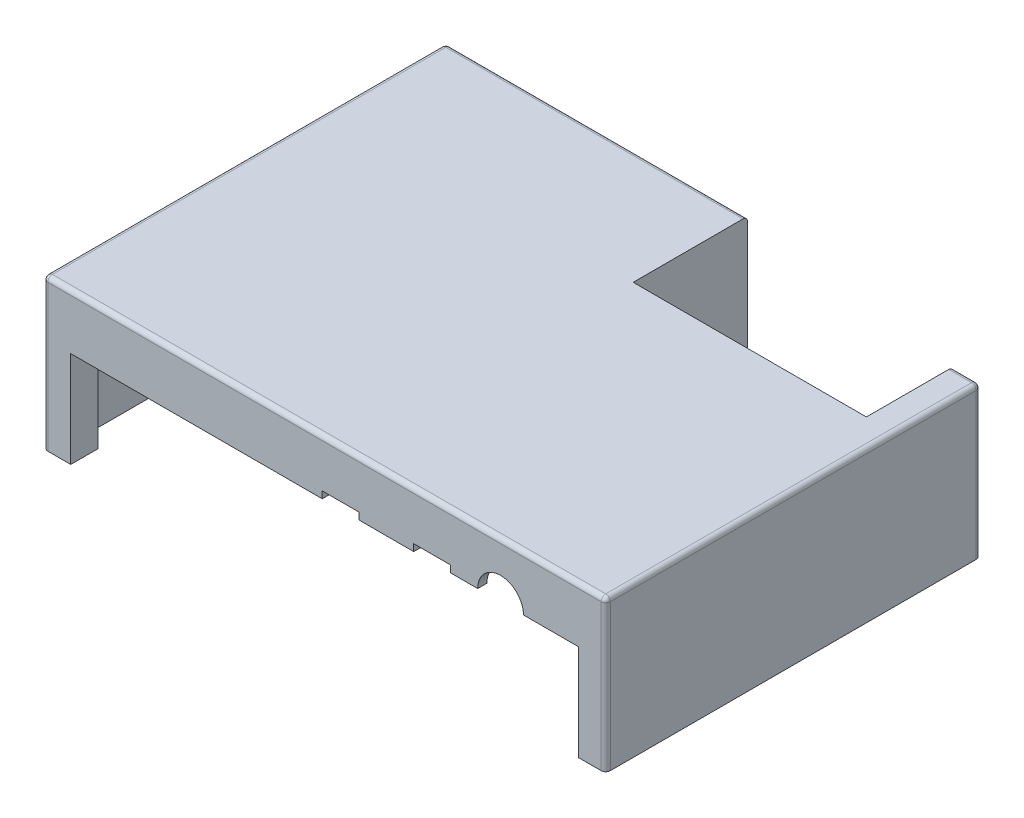
SolidWorks part; units mm, degrees
ref_plane "Front Plane" through (0, 0, 0) normal (0, 0, 1) x (1, 0, 0)
ref_plane "Top Plane" through (0, 0, 0) normal (0, 1, 0) x (1, 0, 0)
ref_plane "Right Plane" through (0, 0, 0) normal (1, 0, 0) x (0, 0, -1)
sketch "Sketch2" plane through (0, 0, 0) normal (0, 1, 0) x (1, 0, 0)
  line L5 (-61.5, 44) -> (61.5, 44)
  line L6 (-61.5, 44) -> (-61.5, -44)
  line L7 (-61.5, -44) -> (61.5, -44)
  line L8 (61.5, 44) -> (61.5, -44)
  line L9 (-61.5, 44) -> (61.5, -44) construction
  line L10 (-61.5, -44) -> (61.5, 44) construction
  point P0 (0, 0)
  dimension "D1" = 123
  dimension "D2" = 88
extrude "Boss-Extrude1" add sketch "Sketch2" against normal blind 2
sketch "Sketch3" plane through (0, 0, 0) normal (0, 1, 0) x (1, 0, 0)
  line L1 (55.5, 44) -> (61.5, 44)
  line L2 (55.5, 44) -> (55.5, 38)
  line L3 (55.5, 38) -> (61.5, 38)
  line L4 (61.5, 44) -> (61.5, 38)
  line L5 (55.5, 44) -> (61.5, 38) construction
  line L6 (55.5, 38) -> (61.5, 44) construction
  line L7 (4.5, 44) -> (55.5, 44)
  line L8 (4.5, 44) -> (4.5, 19)
  line L9 (4.5, 19) -> (55.5, 19)
  line L10 (55.5, 44) -> (55.5, 19)
  line L11 (4.5, 44) -> (55.5, 19) construction
  line L12 (4.5, 19) -> (55.5, 44) construction
  point P0 (58.5, 41)
  point P7 (30, 31.5)
  line M7 (61.5, -44) -> (61.5, 44)
  line M8 (61.5, 44) -> (-61.5, 44)
  dimension "D1" = 6
  dimension "D2" = 6
  dimension "D3" = 51
  dimension "D4" = 25
extrude "Cut-Extrude1" cut sketch "Sketch3" against normal blind 2 contours L10 L2 L8 L9 M8 | L2 L3 M7 M8
sketch "Sketch4" plane through (0, 0, 0) normal (0, 1, 0) x (1, 0, 0)
  line L0 (55.5, -38) -> (61.5, -38)
  line L1 (55.5, 38) -> (61.5, 38)
  line L2 (55.5, 38) -> (55.5, 32)
  line L3 (55.5, 32) -> (61.5, 32)
  line L4 (61.5, 38) -> (61.5, 32)
  line L5 (55.5, 38) -> (61.5, 32) construction
  line L6 (55.5, 32) -> (61.5, 38) construction
  line L7 (61.5, 32) -> (59.5, 32)
  line L8 (61.5, 32) -> (61.5, -38)
  line L9 (61.5, -38) -> (59.5, -38)
  line L10 (59.5, 32) -> (59.5, -38)
  line L11 (61.5, 32) -> (59.5, -38) construction
  line L12 (61.5, -38) -> (59.5, 32) construction
  line L13 (55.5, -38) -> (55.5, -44)
  line L14 (55.5, -44) -> (61.5, -44)
  line L15 (61.5, -38) -> (61.5, -44)
  line L16 (55.5, -38) -> (61.5, -44) construction
  line L17 (55.5, -44) -> (61.5, -38) construction
  line L18 (61.5, -44) -> (59.5, -44)
  line L24 (-55.5, -42) -> (55.5, -42)
  line L25 (-55.5, -42) -> (-55.5, -44)
  line L26 (-61.5, -38) -> (-55.5, -38)
  line L27 (-61.5, -38) -> (-61.5, -44)
  line L28 (-61.5, -44) -> (-55.5, -44)
  line L29 (-55.5, -38) -> (-55.5, -44)
  line L30 (-61.5, -38) -> (-55.5, -44) construction
  line L31 (-61.5, -44) -> (-55.5, -38) construction
  line L32 (-55.5, -44) -> (-57.5, -44)
  line L37 (-55.5, -44) -> (55.5, -44)
  line L38 (55.5, -42) -> (55.5, -44)
  line L39 (-55.5, -42) -> (55.5, -44) construction
  line L44 (-61.5, 44) -> (-61.5, 38)
  line L45 (-55.5, -44) -> (55.5, -42) construction
  line L46 (-61.5, 38) -> (-59.5, 38)
  line L47 (-61.5, 44) -> (-55.5, 44)
  line L49 (-61.5, 38) -> (-55.5, 38)
  line L50 (-55.5, 44) -> (-55.5, 38)
  line L51 (-61.5, 44) -> (-55.5, 38) construction
  line L52 (-61.5, 38) -> (-55.5, 44) construction
  line L53 (-55.5, 38) -> (-57.5, 38)
  line L54 (-61.5, 38) -> (-61.5, -38)
  line L55 (-61.5, -38) -> (-59.5, -38)
  line L56 (-59.5, 38) -> (-59.5, -38)
  line L57 (-55.5, 44) -> (4.5, 44)
  line L58 (-55.5, 44) -> (-55.5, 42)
  line L59 (-55.5, 42) -> (4.5, 42)
  line L60 (4.5, 44) -> (4.5, 42)
  line L61 (2.5, 42) -> (4.5, 42)
  line L62 (2.5, 42) -> (2.5, 17)
  line L63 (2.5, 17) -> (4.5, 17)
  line L64 (4.5, 42) -> (4.5, 17)
  line L65 (4.5, 19) -> (55.5, 19)
  line L66 (4.5, 19) -> (4.5, 17)
  line L67 (4.5, 17) -> (55.5, 17)
  line L68 (55.5, 19) -> (55.5, 17)
  point P0 (55.5, 38)
  point P8 (54.7765, -38.1599)
  point P14 (60.5, -3)
  point P22 (0, -43)
  point P24 (58.5, -41)
  point P31 (-63.8243, -36.7219)
  point P56 (-56.1941, 43.3453)
  line M43 (4.5, 19) -> (4.5, 44)
  line M44 (4.5, 44) -> (-61.5, 44)
  line M45 (-61.5, 44) -> (-61.5, -44)
  line M46 (-61.5, -44) -> (61.5, -44)
  line M47 (61.5, -44) -> (61.5, 38)
  line M48 (61.5, 38) -> (55.5, 38)
  line M49 (55.5, 38) -> (55.5, 19)
  line M50 (55.5, 19) -> (4.5, 19)
  dimension "D1" = 6
  dimension "D2" = 6
  dimension "D4" = 2
  dimension "D5" = 2
  dimension "D7" = 2
  dimension "D10" = 2
  dimension "D3" = 6
  dimension "D6" = 6
  dimension "D8" = 6
  dimension "D9" = 6
  dimension "D11" = 6
  dimension "D12" = 6
  dimension "D13" = 2
  dimension "D14" = 111
  dimension "D15" = 2
  dimension "D16" = 76
  dimension "D17" = 60
  dimension "D18" = 2
  dimension "D19" = 25
  dimension "D20" = 2
  dimension "D21" = 2
  dimension "D22" = 51
extrude "Boss-Extrude2" add sketch "Sketch4" against normal blind 33 contours L50 L59 M43 M44 | L50 L46 L49 M44 M45 | L56 L46 L26 M45 | L68 L64 L67 M50 | L3 M49 M47 M48 | L29 L26 L28 L25 M45 M46 | L24 L25 L13 M46 | L0 L13 L14 M46 M47 | L3 L10 L0 M47
sketch "Sketch5" plane through (0, 0, -44) normal (0, 0, -1) x (-1, 0, 0)
  line L0 (-4.5, -33) -> (61.5, -33) construction
  line L1 (61.5, -33) -> (61.5, 0) construction
  line L3 (10.5, -9) -> (23.5, -9)
  line L4 (10.5, -9) -> (10.5, -17)
  line L5 (10.5, -17) -> (23.5, -17)
  line L6 (23.5, -9) -> (23.5, -17)
  circle A0 centre (35.5, -12) radius 3
  point P10 (23.5, -13)
  dimension "D1" = 6
  dimension "D2" = 21
  dimension "D3" = 26
  dimension "D4" = 13
  dimension "D5" = 8
  dimension "D6" = 38
  dimension "D7" = 20
extrude "Cut-Extrude2" cut sketch "Sketch5" against normal up to surface (2 mm away) and the other way through all contours L6 L3 L4 L5 | A0 up to face at (-26.5, -17.5, -42)
sketch "Sketch6" plane through (0, 0, 44) normal (0, 0, 1) x (1, 0, 0)
  line L0 (-61.5, -33) -> (61.5, -33) construction
  line L1 (-55.5, -12) -> (55.5, -12)
  line L2 (-55.5, -12) -> (-55.5, -33)
  line L3 (-55.5, -33) -> (55.5, -33)
  line L4 (55.5, -12) -> (55.5, -33)
  line L5 (-61.5, -33) -> (-61.5, 0) construction
  dimension "D3" = 6
  dimension "D1" = 111
  dimension "D2" = 21
extrude "Cut-Extrude3" cut sketch "Sketch6" against normal up to surface (2 mm away) up to face at (0, -17.5, 42)
sketch "Sketch7" plane through (0, 0, 44) normal (0, 0, 1) x (1, 0, 0)
  line L0 (33.5, -12) -> (43.5, -12)
  line L1 (-0.5, -10.5) -> (7.5, -10.5)
  line L2 (61.5, -33) -> (61.5, 0) construction
  line L3 (55.5, -12) -> (-55.5, -12) construction
  line L4 (19.5, -10.5) -> (27.5, -10.5)
  line L5 (19.5, -10.5) -> (19.5, -12)
  line L6 (19.5, -12) -> (27.5, -12)
  line L7 (27.5, -10.5) -> (27.5, -12)
  line L8 (-0.5, -10.5) -> (-0.5, -12)
  line L9 (-0.5, -12) -> (7.5, -12)
  line L10 (7.5, -10.5) -> (7.5, -12)
  arc A0 (43.5, -12) -> (33.5, -12) centre (38.5, -12) ccw
  dimension "D1" = 10
  dimension "D2" = 23
  dimension "D3" = 8
  dimension "D4" = 1.5
  dimension "D5" = 34
  dimension "D7" = 20
  dimension "D6" = 2
extrude "Cut-Extrude4" cut sketch "Sketch7" against normal up to surface (2 mm away) up to face at (0, -7, 42)
sketch "Sketch10" plane through (0, -33, 0) normal (0, -1, 0) x (1, 0, 0)
  line L0 (-61.5, 44) -> (-55.5, 38) construction
  line L1 (-55.5, 38) -> (-55.5, 44) construction
  line L3 (-55.5, -38) -> (-61.5, -44) construction
  line L4 (55.5, -32) -> (61.5, -38) construction
  line L5 (61.5, 44) -> (55.5, 38) construction
  point P4 (-58.5, 41)
  point P9 (-58.5, -41)
  point P17 (58.5, -35)
  point P22 (58.5, 41)
hole_wizard "Ø3.0mm Dowel Hole2" positions "Sketch13" profile "Sketch14" hole size "Ø3.0" standard "ANSI Metric"
sketch "Sketch13" plane through (0, -33, 0) normal (0, -1, 0) x (-1, 0, 0)
  point P0 (58.5, -41)
  point P3 (58.5, 41)
  point P6 (-58.5, 35)
  point P9 (-58.5, -41)
sketch "Sketch14" plane through (-58.5, -33, 41) normal (1, 0, 0) x (0, 0, -1)
  line L0 (0, 0) -> (0, 15.9013)
  line L1 (0, 15.9013) -> (1.5, 15)
  line L2 (1.5, 15) -> (1.5, 0)
  line L5 (1.5, 0) -> (0, 0)
  line L10 (0, 15.9013) -> (-1.5, 15) construction
  line L11 (0, -6.35) -> (0, 107.95) construction
  dimension "Hole Dia." = 3
  dimension "Hole Depth" = 15
  dimension "Drill Angle" = 118
sketch "Sketch15" plane through (-61.5, 0, 0) normal (-1, 0, 0) x (0, 0, 1)
  line L0 (-44, -33) -> (44, -33) construction
  line L1 (14, -27) -> (26, -27) construction
  line L2 (14, -27) -> (14, -33) construction
  line L3 (14, -33) -> (26, -33) construction
  line L4 (26, -27) -> (26, -33) construction
  line L5 (44, -33) -> (44, 0) construction
  line L6 (14, -27) -> (26, -33) construction
  line L7 (26, -27) -> (14, -33) construction
  line L10 (17, -30) -> (17, -33)
  line L11 (17, -33) -> (23, -33)
  line L12 (23, -30) -> (23, -33)
  arc A0 (23, -30) -> (17, -30) centre (20, -30) ccw
  point P11 (20, -30)
  line M8 (-44, -33) -> (44, -33)
  dimension "D4" = 6
  dimension "D1" = 12
  dimension "D2" = 6
  dimension "D3" = 18
  dimension "D5" = 6
extrude "Cut-Extrude10" cut sketch "Sketch15" against normal up to surface (2 mm away) contours L12 A0 L10 M8
fillet "Fillet1" radius 1 9 edges at (-28.5, 0, -44) (61.5, -16.5, -38) (58.5, 0, -38) (0, 0, 44) (-61.5, 0, 0) (61.5, 0, 3) (61.5, -16.5, 44) (-61.5, -16.5, 44) (-61.5, -16.5, -44)
equation "\"D17@Sketch4\"=123-51-12"
equation "\"D19@Sketch4\"=25"
equation "\"D1@Sketch6\"=123-12"
equation "\"D2@Sketch6\"=21"
equation "\"D5@Sketch7\"=28+6"
